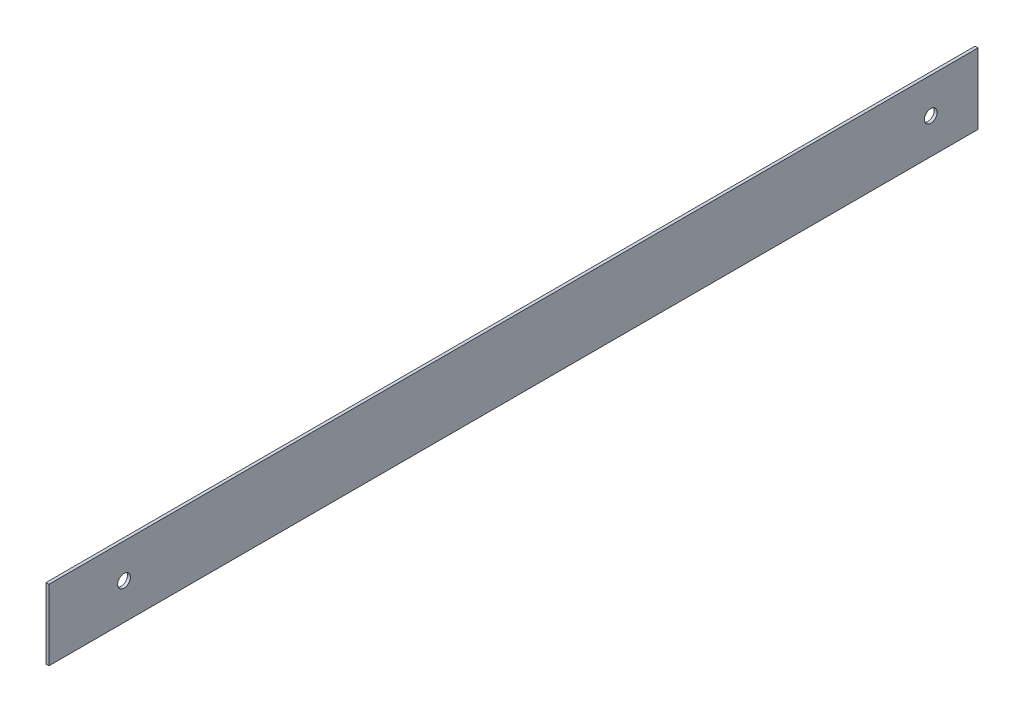
SolidWorks part; units mm, degrees
ref_plane "Front Plane" through (0, 0, 0) normal (0, 0, 1) x (1, 0, 0)
ref_plane "Top Plane" through (0, 0, 0) normal (0, 1, 0) x (1, 0, 0)
ref_plane "Right Plane" through (0, 0, 0) normal (1, 0, 0) x (0, 0, -1)
sketch "Sketch1" plane through (0, 0, 0) normal (1, 0, 0) x (0, 0, -1)
  line L1 (0, 0) -> (1000, 0)
  line L2 (0, 0) -> (0, -76.073)
  line L3 (0, -76.073) -> (1000, -76.073)
  line L4 (1000, 0) -> (1000, -76.073)
  dimension "D1" = 76.073
  dimension "D2" = 1000
extrude "Boss-Extrude1" add sketch "Sketch1" along normal blind 3.175
sketch "Sketch2" plane through (0, 0, 0) normal (0, 0, 1) x (1, 0, 0)
  line L0 (1.5875, 0) -> (1.5875, -76.073) construction
  line L1 (3.175, 0) -> (0, 0) construction
  line L2 (3.175, -76.073) -> (0, -76.073) construction
sketch "Sketch3" plane through (0, 0, -1000) normal (0, 0, -1) x (-1, 0, 0)
  line L0 (-1.5875, 0) -> (-1.5875, -76.073) construction
  line L1 (-3.175, 0) -> (0, 0) construction
  line L2 (-3.175, -76.073) -> (0, -76.073) construction
hole_wizard "1/4 NPT Tapped Hole3" positions "3DSketch6" profile "Sketch13" size "1/4" standard "ANSI Inch" end condition through all
sketch3d "3DSketch6"
  point P0 (3.175, -37.1876, -80.8358)
sketch "Sketch13" plane through (3.175, -37.1876, -80.8358) normal (0, 1, 0) x (0, 0, -1)
  line L0 (0, 0) -> (0, 3.175)
  line L1 (0, 3.175) -> (5.5626, 3.175)
  line L2 (-6.558, 9.906) -> (-6.8546, 0) construction
  line L3 (5.5626, 3.175) -> (5.5626, 9.906)
  line L4 (5.5626, 9.906) -> (6.558, 9.906)
  line L5 (6.558, 9.906) -> (6.8546, 0)
  line L7 (6.8546, 0) -> (0, 0)
  line L8 (0, -6.35) -> (0, 107.95) construction
  line L11 (-5.5626, 9.906) -> (-6.558, 9.906) construction
  dimension "Thru Tap Drill Dia." = 11.1252
  dimension "Thru Tap Drill Depth" = 3.175
  dimension "Thread Dia." = 13.7092
  dimension "Thread Angle" = 3.43
  dimension "Thread Depth" = 9.906
sketch "Sketch14" plane through (3.175, 0, 0) normal (1, 0, 0) x (0, 0, -1)
  line L0 (1000, -38.0365) -> (949.2, -38.0365) construction
  line L1 (1000, 0) -> (1000, -76.073) construction
hole_wizard "1/4 NPT Tapped Hole4" positions "3DSketch7" profile "Sketch15" size "1/4" standard "ANSI Inch" end condition through all
sketch3d "3DSketch7"
  point P0 (3.175, -38.0365, -949.2)
sketch "Sketch15" plane through (3.175, -38.0365, -949.2) normal (0, 1, 0) x (0, 0, -1)
  line L0 (0, 0) -> (0, 3.175)
  line L1 (0, 3.175) -> (5.5626, 3.175)
  line L2 (-6.558, 9.906) -> (-6.8546, 0) construction
  line L3 (5.5626, 3.175) -> (5.5626, 9.906)
  line L4 (5.5626, 9.906) -> (6.558, 9.906)
  line L5 (6.558, 9.906) -> (6.8546, 0)
  line L7 (6.8546, 0) -> (0, 0)
  line L8 (0, -6.35) -> (0, 107.95) construction
  line L11 (-5.5626, 9.906) -> (-6.558, 9.906) construction
  dimension "Thru Tap Drill Dia." = 11.1252
  dimension "Thru Tap Drill Depth" = 3.175
  dimension "Thread Dia." = 13.7092
  dimension "Thread Angle" = 3.43
  dimension "Thread Depth" = 9.906
